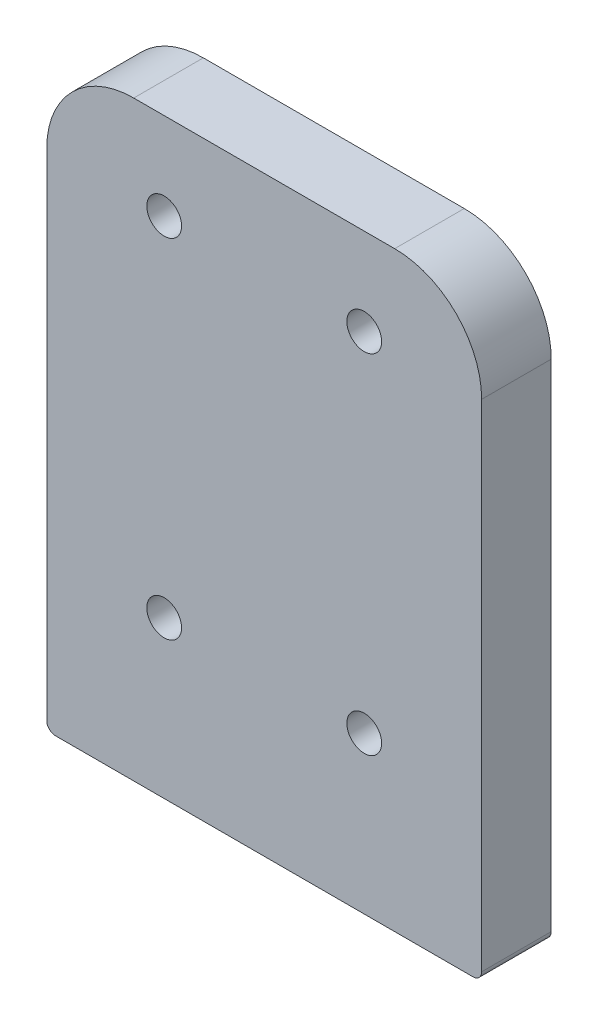
SolidWorks part; units mm, degrees
material "6061 合金"
ref_plane "前视基准面" through (0, 0, 0) normal (0, 0, 1) x (1, 0, 0)
ref_plane "上视基准面" through (0, 0, 0) normal (0, 1, 0) x (1, 0, 0)
ref_plane "右视基准面" through (0, 0, 0) normal (1, 0, 0) x (0, 0, -1)
sketch "草图1" plane through (0, 0, 0) normal (0, 0, 1) x (1, 0, 0)
  line L1 (-25, 34) -> (25, 34)
  line L2 (-25, 34) -> (-25, -34)
  line L3 (-25, -34) -> (25, -34)
  line L4 (25, 34) -> (25, -34)
  line L5 (-25, 34) -> (25, -34) construction
  line L6 (-25, -34) -> (25, 34) construction
  point P0 (0, 0)
  dimension "D1" = 68
  dimension "D2" = 50
extrude "凸台-拉伸1" add sketch "草图1" along normal blind 8
sketch "草图2" plane through (0, 0, 8) normal (0, 0, 1) x (1, 0, 0)
  line L0 (0, 51.9871) -> (0, -65.963) construction
  line L1 (-25, -34) -> (25, -34) construction
  circle A0 centre (-11.5, -16) radius 2
  circle A1 centre (-11.5, 24) radius 2
  circle A2 centre (11.5, 24) radius 2
  circle A3 centre (11.5, -16) radius 2
  dimension "D1" = 4
  dimension "D2" = 23
  dimension "D3" = 4
  dimension "D4" = 23
  dimension "D5" = 40
  dimension "D6" = 18
extrude "切除-拉伸1" cut sketch "草图2" against normal through all
sketch "草图4" plane through (0, -34, 0) normal (0, -1, 0) x (1, 0, 0)
  line L0 (-25, 4) -> (25, 4) construction
  line L1 (-25, 8) -> (-25, 0) construction
  line L2 (25, 8) -> (25, 0) construction
  line L3 (0, 15.3062) -> (0, -10.8088) construction
  point P9 (-20, 4)
  point P10 (21, 4)
  point P11 (0, 0)
  point P12 (12.5, 4)
  point P13 (-12.5, 4)
  point P14 (20, 4)
  dimension "D1" = 25
  dimension "D3" = 40
hole_wizard "M4 螺纹孔1" positions "3D草图1" profile "草图5" tap size "M4" standard "GB"
sketch3d "3D草图1"
  point P0 (-20, -34, 4)
  point P3 (20, -34, 4)
sketch "草图5" plane through (-20, -34, 4) normal (1, 0, 0) x (0, 0, -1)
  line L0 (0, 0) -> (0, 11.0914)
  line L1 (0, 11.0914) -> (1.65, 10.1)
  line L2 (1.65, 10.1) -> (1.65, 0.375)
  line L3 (1.65, 0.375) -> (2.025, 0)
  line L5 (2.025, 0) -> (0, 0)
  line L6 (-1.65, 0.375) -> (-2.025, 0) construction
  line L10 (0, 11.0914) -> (-1.65, 10.1) construction
  line L11 (0, -6.35) -> (0, 107.95) construction
  dimension "螺纹孔钻头直径" = 3.3
  dimension "螺纹孔钻头深度" = 10.1
  dimension "近端锥形沉头孔直径" = 4.05
  dimension "近端锥形沉头孔角度" = 90
  dimension "导头角度" = 118
cosmetic thread "孔螺蚊线1" parameters "D1"=8, "D2"=4
cosmetic thread "孔螺蚊线2" parameters "D1"=8, "D2"=4
hole_wizard "大小mm 暗销孔1" positions "3D草图2" profile "草图6" hole size "Ø3.0" standard "GB"
sketch3d "3D草图2"
  point P0 (-12.5, -34, 4)
  point P3 (12.5, -34, 4)
sketch "草图6" plane through (-12.5, -34, 4) normal (1, 0, 0) x (0, 0, -1)
  line L0 (0, 0) -> (0, 8.9013)
  line L1 (0, 8.9013) -> (1.5, 8)
  line L2 (1.5, 8) -> (1.5, 0)
  line L5 (1.5, 0) -> (0, 0)
  line L10 (0, 8.9013) -> (-1.5, 8) construction
  line L11 (0, -6.35) -> (0, 107.95) construction
  dimension "孔直径" = 3
  dimension "孔深度" = 8
  dimension "导头角度" = 118
fillet "圆角1" radius 10 2 edges at (-25, 34, 4) (25, 34, 4)
fillet "圆角2" radius 1 2 edges at (-25, -34, 4) (25, -34, 4)
